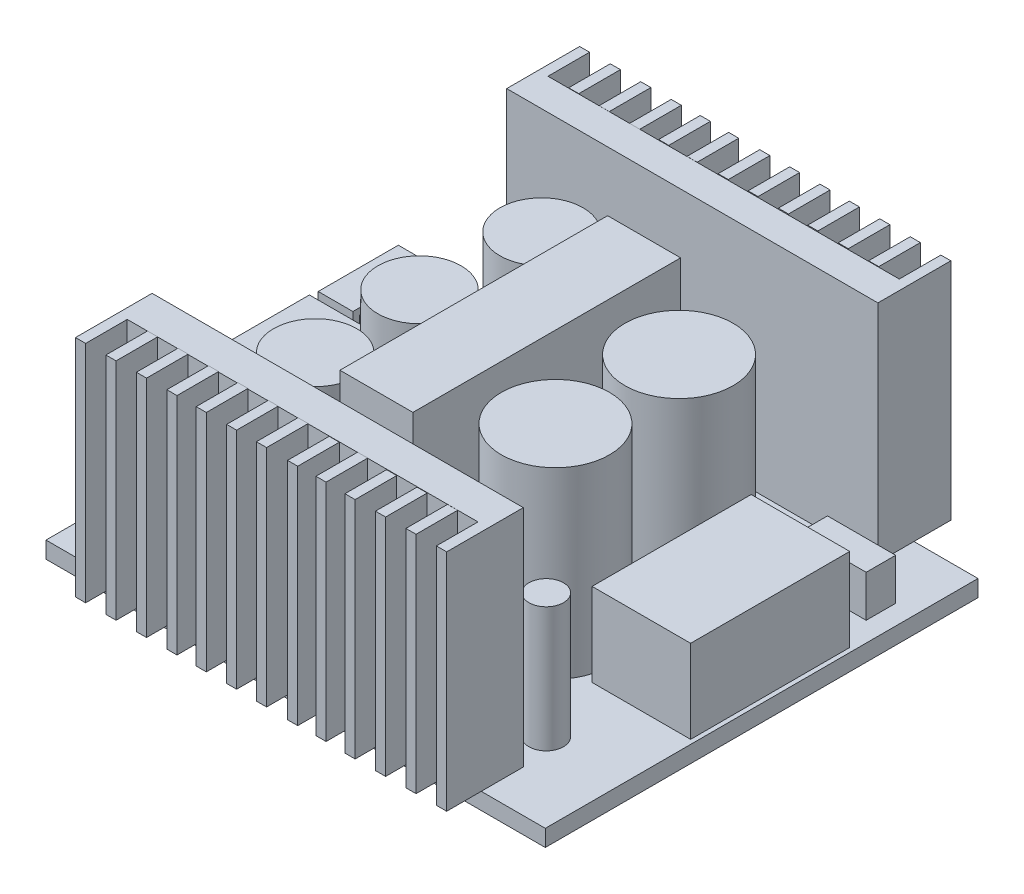
SolidWorks part; units mm, degrees
ref_plane "Ebene vorne" through (0, 0, 0) normal (0, 0, 1) x (1, 0, 0)
ref_plane "Ebene oben" through (0, 0, 0) normal (0, 1, 0) x (1, 0, 0)
ref_plane "Ebene rechts" through (0, 0, 0) normal (1, 0, 0) x (0, 0, -1)
sketch "Skizze1" plane through (0, 0, 0) normal (0, 1, 0) x (1, 0, 0)
  line L1 (-30, -26) -> (30, -26)
  line L2 (-30, -26) -> (-30, 26)
  line L3 (-30, 26) -> (30, 26)
  line L4 (30, -26) -> (30, 26)
  line L5 (-30, -26) -> (30, 26) construction
  line L6 (-30, 26) -> (30, -26) construction
  point P0 (0, 0)
  dimension "D1" = 60
  dimension "D2" = 52
extrude "Aufsatz-Linear austragen1" add sketch "Skizze1" along normal blind 2
sketch "Skizze2" plane through (0, 2, 0) normal (0, 1, 0) x (1, 0, 0)
  line L1 (-29.5156, 6.2263) -> (-25.3443, 6.2263)
  line L2 (-29.5156, 6.2263) -> (-29.5156, 15.8557)
  line L3 (-29.5156, 15.8557) -> (-25.3443, 15.8557)
  line L4 (-25.3443, 6.2263) -> (-25.3443, 15.8557)
  line L5 (-29.5156, 6.2263) -> (-25.3443, 15.8557) construction
  line L6 (-29.5156, 15.8557) -> (-25.3443, 6.2263) construction
  line L30 (-24.5521, 6.2096) -> (-20.3807, 6.2096)
  line L31 (-24.5521, 6.2096) -> (-24.5521, 15.839)
  line L32 (-24.5521, 15.839) -> (-20.3807, 15.839)
  line L33 (-20.3807, 6.2096) -> (-20.3807, 15.839)
  point P0 (-27.43, 11.041)
  point P9 (-20.865, 15.8009)
  point P10 (0, 0)
  point P11 (-25.3443, 6.2263)
  point P12 (-25.3907, -3.9688)
  point P18 (0, 28.6409)
extrude "Aufsatz-Linear austragen2" add sketch "Skizze2" along normal blind 10 contours L1 L4 L3 L2 | L30 L33 L32 L31
sketch "Skizze3" plane through (0, 2, 0) normal (0, 1, 0) x (1, 0, 0)
  line L0 (17.6329, -8.011) -> (29.4767, -8.011)
  line L7 (17.6329, -8.011) -> (17.6329, 11.1107)
  line L8 (17.6329, 11.1107) -> (29.4767, 11.1107)
  line L9 (29.4767, -8.011) -> (29.4767, 11.1107)
  line L10 (-29.6816, -13.7875) -> (-17.8378, -13.7875)
  line L11 (-29.6816, -13.7875) -> (-29.6816, 5.3341)
  line L12 (-29.6816, 5.3341) -> (-17.8378, 5.3341)
  line L13 (-17.8378, -13.7875) -> (-17.8378, 5.3341)
  point P1 (0, 0)
  point P9 (27.3403, -7.4992)
  point P10 (-28.1151, 1.854)
extrude "Aufsatz-Linear austragen3" add sketch "Skizze3" along normal blind 10
sketch "Skizze4" plane through (0, 2, 0) normal (0, 1, 0) x (1, 0, 0)
  circle A0 centre (20.5365, -16.4258) radius 2.0723
extrude "Aufsatz-Linear austragen4" add sketch "Skizze4" along normal blind 15
sketch "Skizze5" plane through (0, 2, 0) normal (0, 1, 0) x (1, 0, 0)
  line L1 (19.4431, 14.9263) -> (27.6341, 14.9263)
  line L2 (19.4431, 14.9263) -> (19.4431, 18.4684)
  line L3 (19.4431, 18.4684) -> (27.6341, 18.4684)
  line L4 (27.6341, 14.9263) -> (27.6341, 18.4684)
  line L5 (19.4431, 14.9263) -> (27.6341, 18.4684) construction
  line L6 (19.4431, 18.4684) -> (27.6341, 14.9263) construction
  point P0 (23.5386, 16.6974)
extrude "Aufsatz-Linear austragen5" add sketch "Skizze5" along normal blind 5
sketch "Skizze6" plane through (0, 2, 0) normal (0, 1, 0) x (1, 0, 0)
  line L1 (-22.3039, 21.6675) -> (22.3039, 21.6675)
  line L2 (-22.3039, 21.6675) -> (-22.3039, 25.4309)
  line L3 (-22.3039, 25.4309) -> (22.3039, 25.4309)
  line L4 (22.3039, 21.6675) -> (22.3039, 25.4309)
  line L5 (-22.3039, 21.6675) -> (22.3039, 25.4309) construction
  line L6 (-22.3039, 25.4309) -> (22.3039, 21.6675) construction
  line L7 (-22.3039, -25.1542) -> (22.3039, -25.1542)
  line L8 (-22.3039, -25.1542) -> (-22.3039, -20.948)
  line L9 (-22.3039, -20.948) -> (22.3039, -20.948)
  line L10 (22.3039, -25.1542) -> (22.3039, -20.948)
  line L11 (-22.3039, -25.1542) -> (22.3039, -20.948) construction
  line L12 (-22.3039, -20.948) -> (22.3039, -25.1542) construction
  point P0 (0, 23.5492)
  point P5 (0, -23.0511)
extrude "Aufsatz-Linear austragen6" add sketch "Skizze6" along normal blind 27
sketch "Skizze7" plane through (0, 2, 0) normal (0, 1, 0) x (1, 0, 0)
  circle A0 centre (-11.6045, 0.4874) radius 5
  circle A1 centre (-10.3048, 13.8558) radius 5
  circle A2 centre (-11.326, -12.324) radius 5
  circle A3 centre (10.7226, 9.3533) radius 6.5
  circle A4 centre (10.4905, -5.2685) radius 6.5
extrude "Aufsatz-Linear austragen7" add sketch "Skizze7" along normal blind 22
sketch "Skizze8" plane through (0, 2, 0) normal (0, 1, 0) x (1, 0, 0)
  line L1 (3.7599, 16.5017) -> (-5.0132, 16.5017)
  line L2 (3.7599, 16.5017) -> (3.7599, -15.6661)
  line L3 (3.7599, -15.6661) -> (-5.0132, -15.6661)
  line L4 (-5.0132, 16.5017) -> (-5.0132, -15.6661)
extrude "Aufsatz-Linear austragen8" add sketch "Skizze8" along normal blind 25
sketch "Skizze9" plane through (0, 0, 25.1542) normal (0, 0, 1) x (1, 0, 0)
  line L1 (-22.3039, 2) -> (22.3039, 2) construction
  line L2 (-22.3039, 29) -> (-21.0839, 29)
  line L3 (-22.3039, 29) -> (-22.3039, 2)
  line L4 (-22.3039, 2) -> (-21.0839, 2)
  line L5 (-21.0839, 29) -> (-21.0839, 2)
  line L6 (-18.6439, 29.014) -> (-17.4239, 29.014)
  line L7 (-18.6439, 29.014) -> (-18.6439, 2.014)
  line L8 (-18.6439, 2.014) -> (-17.4239, 2.014)
  line L9 (-17.4239, 29.014) -> (-17.4239, 2.014)
  line L10 (-14.9839, 29.0484) -> (-13.7639, 29.0484)
  line L11 (-14.9839, 29.0484) -> (-14.9839, 2.0484)
  line L12 (-14.9839, 2.0484) -> (-13.7639, 2.0484)
  line L13 (-13.7639, 29.0484) -> (-13.7639, 2.0484)
  line L14 (-11.3239, 29.0624) -> (-10.1039, 29.0624)
  line L15 (-11.3239, 29.0624) -> (-11.3239, 2.0624)
  line L16 (-11.3239, 2.0624) -> (-10.1039, 2.0624)
  line L17 (-10.1039, 29.0624) -> (-10.1039, 2.0624)
  line L18 (-7.7969, 29.0656) -> (-6.5769, 29.0656)
  line L19 (-7.7969, 29.0656) -> (-7.7969, 2.0656)
  line L20 (-7.7969, 2.0656) -> (-6.5769, 2.0656)
  line L21 (-6.5769, 29.0656) -> (-6.5769, 2.0656)
  line L22 (-4.1369, 29.0475) -> (-2.9385, 29.0475)
  line L23 (-4.1369, 29.0475) -> (-4.1369, 2.0796)
  line L24 (-4.1369, 2.0796) -> (-2.9385, 2.0796)
  line L25 (-2.9385, 29.0475) -> (-2.9385, 2.0796)
  line L26 (-0.5596, 29.0312) -> (0.6604, 29.0312)
  line L27 (-0.5596, 29.0312) -> (-0.5596, 2.0312)
  line L28 (-0.5596, 2.0312) -> (0.6604, 2.0312)
  line L29 (0.6604, 29.0312) -> (0.6604, 2.0312)
  line L30 (3.1831, 28.9624) -> (4.4031, 28.9624)
  line L31 (3.1831, 28.9624) -> (3.1831, 1.9624)
  line L32 (3.1831, 1.9624) -> (4.4031, 1.9624)
  line L33 (4.4031, 28.9624) -> (4.4031, 1.9624)
  line L34 (10.0822, 28.9414) -> (11.3022, 28.9414)
  line L35 (10.0822, 28.9414) -> (10.0822, 1.9414)
  line L36 (10.0822, 1.9414) -> (11.3022, 1.9414)
  line L37 (11.3022, 28.9414) -> (11.3022, 1.9414)
  line L38 (13.7422, 28.9554) -> (14.9622, 28.9554)
  line L39 (13.7422, 28.9554) -> (13.7422, 1.9554)
  line L40 (13.7422, 1.9554) -> (14.9622, 1.9554)
  line L41 (14.9622, 28.9554) -> (14.9622, 1.9554)
  line L42 (17.4022, 28.9898) -> (18.6222, 28.9898)
  line L43 (17.4022, 28.9898) -> (17.4022, 1.9898)
  line L44 (17.4022, 1.9898) -> (18.6222, 1.9898)
  line L45 (18.6222, 28.9898) -> (18.6222, 1.9898)
  line L50 (6.5913, 29.014) -> (7.8113, 29.014)
  line L51 (6.5913, 29.014) -> (6.5913, 2.014)
  line L52 (6.5913, 2.014) -> (7.8113, 2.014)
  line L53 (7.8113, 29.014) -> (7.8113, 2.014)
  line L54 (-30, 2) -> (30, 2) construction
  line L55 (22.3039, 29) -> (21.0659, 29)
  line L56 (22.3039, 29) -> (22.3039, 2)
  line L57 (22.3039, 2) -> (21.0659, 2)
  line L58 (21.0659, 29) -> (21.0659, 2)
  dimension "D1" = 1.22
  dimension "D2" = 1.22
  dimension "D3" = 2.44
  dimension "D4" = 2.44
  dimension "D5" = 2.44
extrude "Aufsatz-Linear austragen9" add sketch "Skizze9" along normal blind 5
sketch "Skizze10" plane through (0, 0, -25.4309) normal (0, 0, -1) x (-1, 0, 0)
  line L4 (-18.6439, 29.0655) -> (-17.4239, 29.0655)
  line L5 (-18.6439, 29.0655) -> (-18.6439, 2.0655)
  line L6 (-18.6439, 2.0655) -> (-17.4239, 2.0655)
  line L7 (-17.4239, 29.0655) -> (-17.4239, 2.0655)
  line L8 (-14.9839, 29.0999) -> (-13.7639, 29.0999)
  line L9 (-14.9839, 29.0999) -> (-14.9839, 2.0999)
  line L10 (-14.9839, 2.0999) -> (-13.7639, 2.0999)
  line L11 (-13.7639, 29.0999) -> (-13.7639, 2.0999)
  line L12 (-11.3239, 29.1139) -> (-10.1039, 29.1139)
  line L13 (-11.3239, 29.1139) -> (-11.3239, 2.1139)
  line L14 (-11.3239, 2.1139) -> (-10.1039, 2.1139)
  line L15 (-10.1039, 29.1139) -> (-10.1039, 2.1139)
  line L16 (-7.7969, 29.1171) -> (-6.5769, 29.1171)
  line L17 (-7.7969, 29.1171) -> (-7.7969, 2.1171)
  line L18 (-7.7969, 2.1171) -> (-6.5769, 2.1171)
  line L19 (-6.5769, 29.1171) -> (-6.5769, 2.1171)
  line L20 (-4.1369, 29.099) -> (-2.9385, 29.099)
  line L21 (-4.1369, 29.099) -> (-4.1369, 2.1311)
  line L22 (-4.1369, 2.1311) -> (-2.9385, 2.1311)
  line L23 (-2.9385, 29.099) -> (-2.9385, 2.1311)
  line L24 (-0.5596, 29.0827) -> (0.6604, 29.0827)
  line L25 (-0.5596, 29.0827) -> (-0.5596, 2.0827)
  line L26 (-0.5596, 2.0827) -> (0.6604, 2.0827)
  line L27 (0.6604, 29.0827) -> (0.6604, 2.0827)
  line L28 (3.1831, 29.0139) -> (4.4031, 29.0139)
  line L29 (3.1831, 29.0139) -> (3.1831, 2.0139)
  line L30 (3.1831, 2.0139) -> (4.4031, 2.0139)
  line L31 (4.4031, 29.0139) -> (4.4031, 2.0139)
  line L32 (10.0822, 28.993) -> (11.3022, 28.993)
  line L33 (10.0822, 28.993) -> (10.0822, 1.993)
  line L34 (10.0822, 1.993) -> (11.3022, 1.993)
  line L35 (11.3022, 28.993) -> (11.3022, 1.993)
  line L36 (13.7422, 29.007) -> (14.9622, 29.007)
  line L37 (13.7422, 29.007) -> (13.7422, 2.007)
  line L38 (13.7422, 2.007) -> (14.9622, 2.007)
  line L39 (14.9622, 29.007) -> (14.9622, 2.007)
  line L40 (17.4022, 29.0414) -> (18.6222, 29.0414)
  line L41 (17.4022, 29.0414) -> (17.4022, 2.0414)
  line L42 (17.4022, 2.0414) -> (18.6222, 2.0414)
  line L43 (18.6222, 29.0414) -> (18.6222, 2.0414)
  line L44 (6.5913, 29.0655) -> (7.8113, 29.0655)
  line L45 (6.5913, 29.0655) -> (6.5913, 2.0655)
  line L46 (6.5913, 2.0655) -> (7.8113, 2.0655)
  line L47 (7.8113, 29.0655) -> (7.8113, 2.0655)
  line L52 (-22.3039, 2) -> (22.3039, 2) construction
  line L53 (-22.3039, 29) -> (-21.1073, 29)
  line L54 (-22.3039, 29) -> (-22.3039, 2)
  line L55 (-22.3039, 2) -> (-21.1073, 2)
  line L56 (-21.1073, 29) -> (-21.1073, 2)
  line L57 (-30, 2) -> (30, 2) construction
  line L58 (22.3039, 29) -> (21.1073, 29)
  line L59 (22.3039, 29) -> (22.3039, 2)
  line L60 (22.3039, 2) -> (21.1073, 2)
  line L61 (21.1073, 29) -> (21.1073, 2)
extrude "Aufsatz-Linear austragen10" add sketch "Skizze10" along normal blind 5
